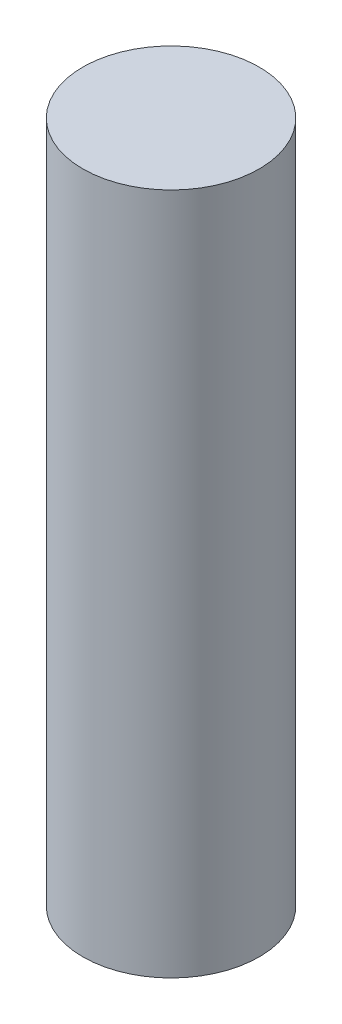
SolidWorks part; units mm, degrees
ref_plane "Front Plane" through (0, 0, 0) normal (0, 0, 1) x (1, 0, 0)
ref_plane "Top Plane" through (0, 0, 0) normal (0, 1, 0) x (1, 0, 0)
ref_plane "Right Plane" through (0, 0, 0) normal (1, 0, 0) x (0, 0, -1)
sketch "Sketch1" plane through (0, 0, 0) normal (0, 1, 0) x (1, 0, 0)
  circle A0 centre (0, 0) radius 9.05
  dimension "D1" = 18.1
extrude "Boss-Extrude1" add sketch "Sketch1" along normal blind 70
